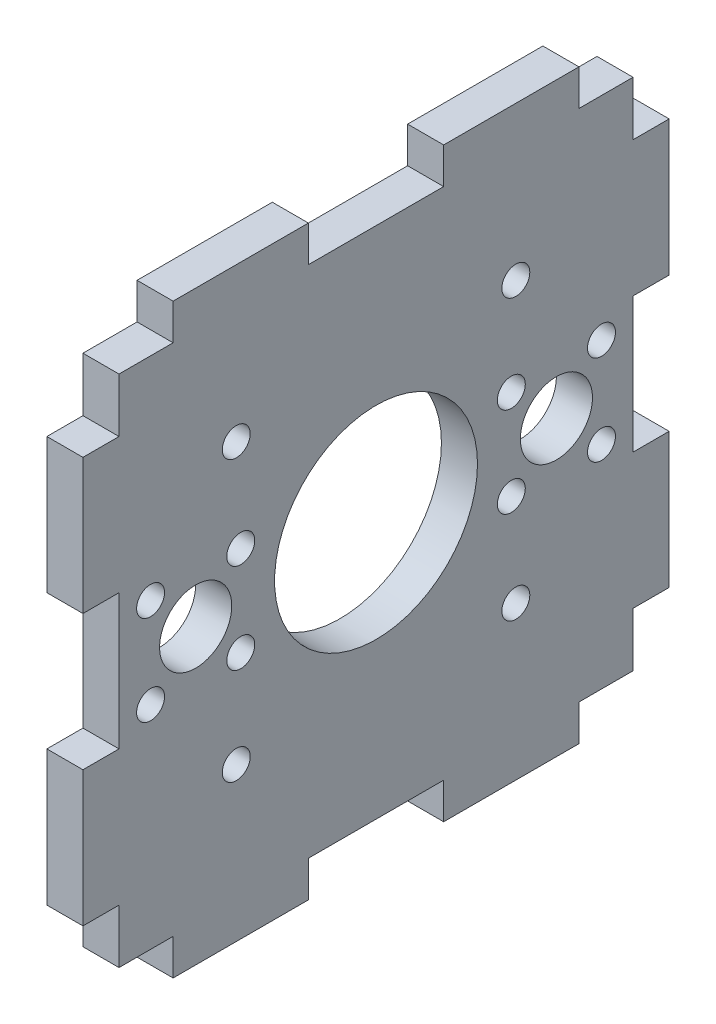
SolidWorks part; units mm, degrees
ref_plane "Front Plane" through (0, 0, 0) normal (0, 0, 1) x (1, 0, 0)
ref_plane "Top Plane" through (0, 0, 0) normal (0, 1, 0) x (1, 0, 0)
ref_plane "Right Plane" through (0, 0, 0) normal (1, 0, 0) x (0, 0, -1)
sketch "Sketch1" plane through (0, 0, 0) normal (1, 0, 0) x (0, 0, -1)
  line L1 (0, 0) -> (65, 0)
  line L2 (0, 0) -> (0, 65)
  line L3 (0, 65) -> (65, 65)
  line L4 (65, 0) -> (65, 65)
  dimension "D1" = 65
  dimension "D2" = 65
extrude "Boss-Extrude1" add sketch "Sketch1" along normal blind 4
sketch "Sketch2" plane through (4, 0, 0) normal (1, 0, 0) x (0, 0, -1)
  line L0 (0, 65) -> (65, 0) construction
  line L2 (17, 17) -> (48, 17) construction
  line L3 (17, 17) -> (17, 48) construction
  line L4 (17, 48) -> (48, 48) construction
  line L5 (48, 17) -> (48, 48) construction
  line L6 (17, 17) -> (48, 48) construction
  line L7 (17, 48) -> (48, 17) construction
  circle A0 centre (17, 48) radius 1.55
  circle A1 centre (32.5, 32.5) radius 11.25
  circle A2 centre (48, 48) radius 1.55
  circle A3 centre (48, 17) radius 1.55
  circle A4 centre (17, 17) radius 1.55
  point P4 (32.5, 32.5)
  dimension "D2" = 3.1
  dimension "D3" = 22.5
  dimension "D1" = 31
  dimension "D4" = 2
  dimension "D5" = 2
extrude "Cut-Extrude1" cut sketch "Sketch2" against normal blind 4 contours A1 | A4 | A2 | A3 | A0
sketch "Sketch3" plane through (4, 0, 0) normal (1, 0, 0) x (0, 0, -1)
  line L0 (65, 65) -> (0, 65) construction
  line L1 (0, 65) -> (10, 65)
  line L2 (0, 65) -> (0, 61)
  line L3 (0, 61) -> (10, 61)
  line L4 (10, 65) -> (10, 61)
  line L5 (25, 65) -> (40, 65)
  line L6 (25, 65) -> (25, 61)
  line L7 (25, 61) -> (40, 61)
  line L8 (40, 65) -> (40, 61)
  line L9 (21.25, 32.5) -> (32.5, 32.5) construction
  line L10 (65, 65) -> (55, 65)
  line L11 (65, 65) -> (65, 61)
  line L12 (65, 61) -> (55, 61)
  line L13 (55, 65) -> (55, 61)
  line L14 (55, 0) -> (55, 4)
  line L15 (65, 4) -> (55, 4)
  line L16 (65, 0) -> (65, 4)
  line L17 (65, 0) -> (55, 0)
  line L18 (40, 0) -> (40, 4)
  line L19 (25, 4) -> (40, 4)
  line L20 (25, 0) -> (25, 4)
  line L21 (25, 0) -> (40, 0)
  line L22 (10, 0) -> (10, 4)
  line L23 (0, 4) -> (10, 4)
  line L24 (0, 0) -> (0, 4)
  line L25 (0, 0) -> (10, 0)
  circle A0 centre (32.5, 32.5) radius 11.25 construction
  dimension "D1" = 15
  dimension "D2" = 15
  dimension "D3" = 10
  dimension "D4" = 10
  dimension "D5" = 4
  dimension "D6" = 4
  dimension "D7" = 4
extrude "Cut-Extrude2" cut sketch "Sketch3" against normal blind 4
sketch "Sketch5" plane through (4, 0, 0) normal (1, 0, 0) x (0, 0, -1)
  line L0 (0, 61) -> (0, 4) construction
  line L1 (0, 61) -> (4, 61)
  line L2 (0, 61) -> (0, 55)
  line L3 (0, 55) -> (4, 55)
  line L4 (4, 61) -> (4, 55)
  line L5 (4, 40) -> (0, 40)
  line L6 (4, 40) -> (4, 25)
  line L7 (4, 25) -> (0, 25)
  line L8 (0, 40) -> (0, 25)
  line L9 (10, 4) -> (0, 4) construction
  line L10 (0, 10) -> (4, 10)
  line L11 (0, 10) -> (0, 4)
  line L12 (0, 4) -> (4, 4)
  line L13 (4, 10) -> (4, 4)
  line L14 (32.5, 4) -> (32.5, 55.5153) construction
  line L15 (40, 4) -> (25, 4) construction
  line L16 (61, 10) -> (61, 4)
  line L17 (65, 4) -> (61, 4)
  line L18 (65, 10) -> (65, 4)
  line L19 (65, 10) -> (61, 10)
  line L20 (65, 40) -> (65, 25)
  line L21 (61, 25) -> (65, 25)
  line L22 (61, 40) -> (61, 25)
  line L23 (61, 40) -> (65, 40)
  line L24 (61, 61) -> (61, 55)
  line L25 (65, 55) -> (61, 55)
  line L26 (65, 61) -> (65, 55)
  line L27 (65, 61) -> (61, 61)
  point P17 (2, 25)
  dimension "D1" = 4
  dimension "D2" = 4
  dimension "D3" = 4
  dimension "D4" = 15
  dimension "D5" = 15
  dimension "D6" = 6
  dimension "D7" = 6
extrude "Cut-Extrude3" cut sketch "Sketch5" against normal blind 4
sketch "Sketch6" plane through (4, 0, 0) normal (1, 0, 0) x (0, 0, -1)
  line L0 (4, 32.5) -> (61, 32.5) construction
  line L1 (4, 25) -> (4, 40) construction
  line L2 (61, 40) -> (61, 25) construction
  line L3 (32.5, 32.5) -> (32.5, 38.7926) construction
  line L4 (7.5, 27.5) -> (17.5, 27.5) construction
  line L5 (7.5, 27.5) -> (7.5, 37.5) construction
  line L6 (7.5, 37.5) -> (17.5, 37.5) construction
  line L7 (17.5, 27.5) -> (17.5, 37.5) construction
  line L8 (7.5, 27.5) -> (17.5, 37.5)
  line L9 (7.5, 37.5) -> (17.5, 27.5)
  circle A0 centre (12.5, 32.5) radius 4
  circle A1 centre (52.5, 32.5) radius 4
  circle A2 centre (7.5, 37.5) radius 1.55
  circle A3 centre (17.5, 37.5) radius 1.55
  circle A4 centre (17.5, 27.5) radius 1.55
  circle A5 centre (7.5, 27.5) radius 1.55
  circle A6 centre (47.5, 27.5) radius 1.55
  circle A7 centre (47.5, 37.5) radius 1.55
  circle A8 centre (57.5, 37.5) radius 1.55
  circle A9 centre (57.5, 27.5) radius 1.55
  dimension "D1" = 8
  dimension "D2" = 8
  dimension "D3" = 8.5
  dimension "D4" = 8.5
  dimension "D7" = 3.1
  dimension "D5" = 10
  dimension "D6" = 10
  dimension "D9" = 2
  dimension "D8" = 2
extrude "Cut-Extrude4" cut sketch "Sketch6" against normal blind 4
